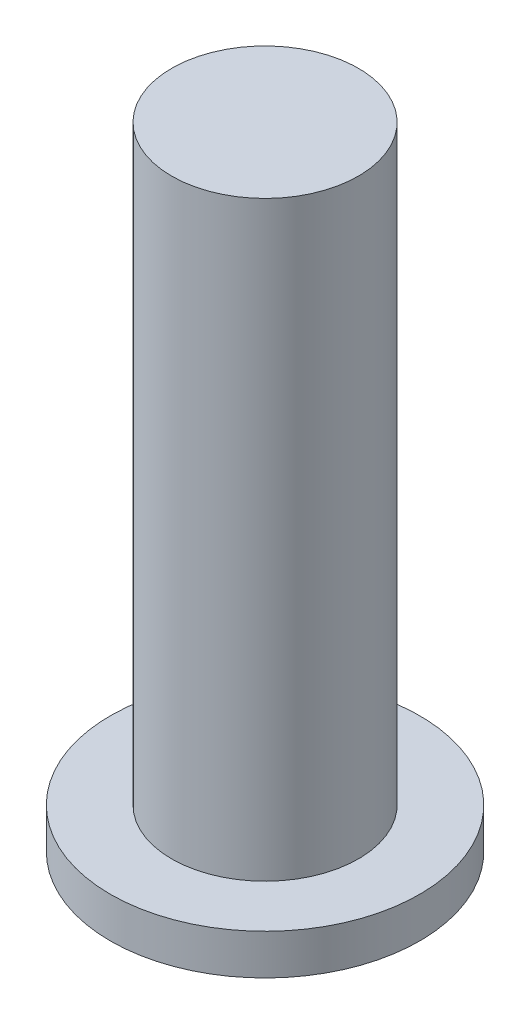
SolidWorks part; units mm, degrees
ref_plane "Front Plane" through (0, 0, 0) normal (0, 0, 1) x (1, 0, 0)
ref_plane "Top Plane" through (0, 0, 0) normal (0, 1, 0) x (1, 0, 0)
ref_plane "Right Plane" through (0, 0, 0) normal (1, 0, 0) x (0, 0, -1)
sketch "Sketch1" plane through (0, 0, 0) normal (0, 1, 0) x (1, 0, 0)
  circle A0 centre (0, 0) radius 6.5
  dimension "D1" = 13
extrude "Boss-Extrude1" add sketch "Sketch1" along normal blind 1.7
sketch "Sketch2" plane through (0, 1.7, 0) normal (0, 1, 0) x (1, 0, 0)
  circle A0 centre (0, 0) radius 3.925
  dimension "D1" = 7.85
extrude "Boss-Extrude2" add sketch "Sketch2" along normal blind 24.85
